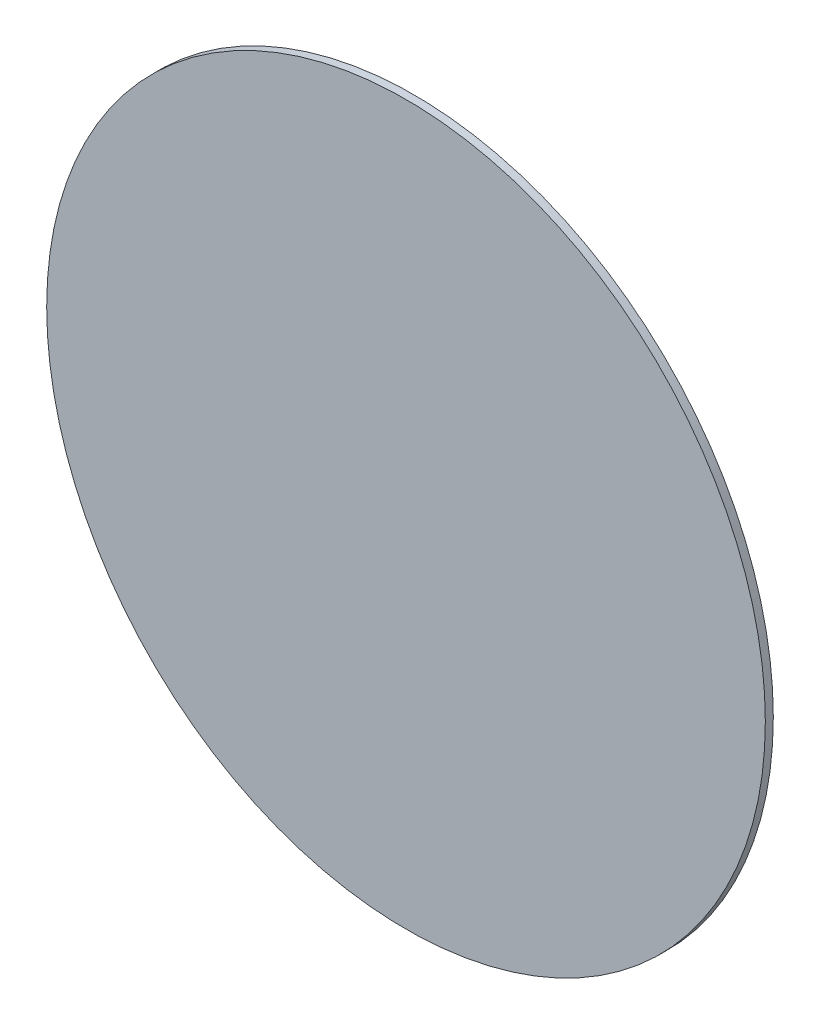
SolidWorks part; units mm, degrees
material "6061-T6 (SS)"
ref_plane "Front Plane" through (0, 0, 0) normal (0, 0, 1) x (1, 0, 0)
ref_plane "Top Plane" through (0, 0, 0) normal (0, 1, 0) x (1, 0, 0)
ref_plane "Right Plane" through (0, 0, 0) normal (1, 0, 0) x (0, 0, -1)
sketch "Sketch1" plane through (0, 0, 0) normal (0, 0, 1) x (1, 0, 0)
  circle A0 centre (0, 0) radius 90 construction
  circle A1 centre (0, 0) radius 90
extrude "Boss-Extrude1" add sketch "Sketch1" along normal up to vertex (2 mm away)
